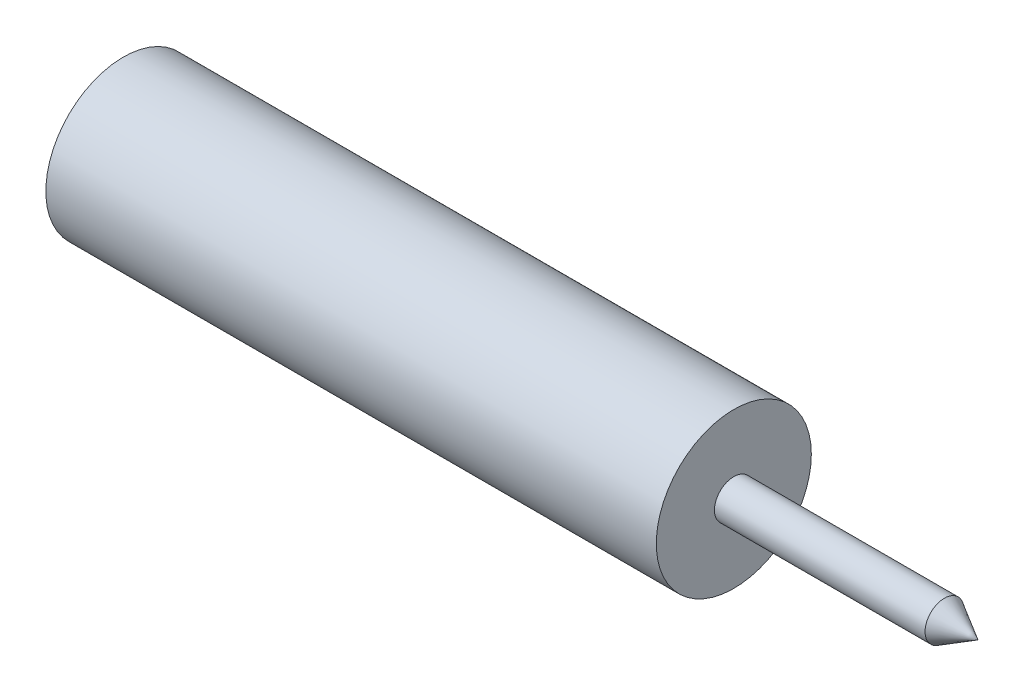
SolidWorks part; units mm, degrees
ref_plane "Front Plane" through (0, 0, 0) normal (0, 0, 1) x (1, 0, 0)
ref_plane "Top Plane" through (0, 0, 0) normal (0, 1, 0) x (1, 0, 0)
ref_plane "Right Plane" through (0, 0, 0) normal (1, 0, 0) x (0, 0, -1)
sketch "Sketch1" plane through (0, 0, 0) normal (0, 0, 1) x (1, 0, 0)
  line L0 (0, 0) -> (0, 6.35)
  line L1 (0, 6.35) -> (50, 6.35)
  line L2 (50, 6.35) -> (50, 1.5875)
  line L3 (50, 1.5875) -> (67.2504, 1.5875)
  line L4 (67.2504, 1.5875) -> (70, 0)
  line L5 (70, 0) -> (0, 0)
  line L6 (0, 0) -> (-18.0909, 0) construction
  dimension "D1" = 30
  dimension "D2" = 3.175
  dimension "D3" = 12.7
  dimension "D4" = 50
  dimension "D5" = 20
revolve "Revolve1" add sketch "Sketch1" angle 360 about L6
